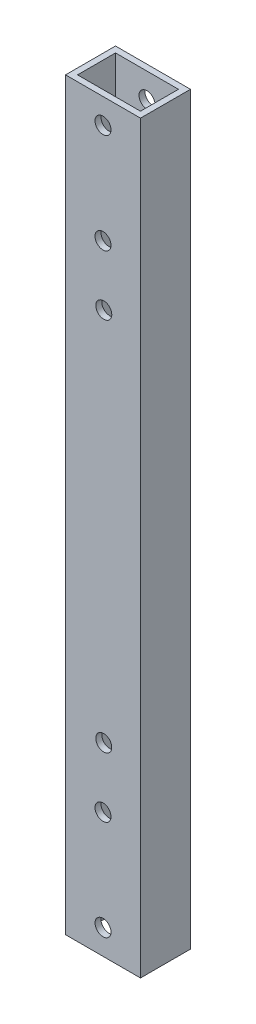
SolidWorks part; units mm, degrees
ref_plane "正面" through (0, 0, 0) normal (0, 0, 1) x (1, 0, 0)
ref_plane "平面" through (0, 0, 0) normal (0, 1, 0) x (1, 0, 0)
ref_plane "右側面" through (0, 0, 0) normal (1, 0, 0) x (0, 0, -1)
sketch "ｽｹｯﾁ1" plane through (0, 0, 0) normal (0, 1, 0) x (1, 0, 0)
  line L0 (-6.3, 3.8) -> (6.3, 3.8)
  line L5 (-7.5, 5) -> (7.5, 5)
  line L6 (-7.5, 5) -> (-7.5, -5)
  line L12 (-7.5, -5) -> (7.5, -5)
  line L13 (7.5, 5) -> (7.5, -5)
  line L14 (-7.5, 5) -> (7.5, -5) construction
  line L15 (-7.5, -5) -> (7.5, 5) construction
  line L16 (6.3, 3.8) -> (6.3, -3.8)
  line L17 (-6.3, -3.8) -> (6.3, -3.8)
  line L18 (-6.3, 3.8) -> (-6.3, -3.8)
  point P0 (0, 0)
  dimension "D1" = 10
  dimension "D2" = 15
  dimension "D3" = 1.2
extrude "ﾎﾞｽ - 押し出し1" add sketch "ｽｹｯﾁ1" along normal mid plane 149.02
sketch "ｽｹｯﾁ3" plane through (0, 0, 5) normal (0, 0, 1) x (1, 0, 0)
  line L0 (0, 74.51) -> (0, 69.51) construction
  line L1 (-7.5, 74.51) -> (7.5, 74.51) construction
  line L2 (0, 69.51) -> (0, 49.51) construction
  circle A0 centre (0, 49.51) radius 1.6
  circle A1 centre (0, 69.51) radius 1.6
  dimension "D3" = 3.2
  dimension "D4" = 3.2
  dimension "D1" = 5
  dimension "D2" = 20
extrude "ｶｯﾄ - 押し出し1" cut sketch "ｽｹｯﾁ3" against normal blind 10
mirror "ﾐﾗｰ1" about plane through (0, 0, 0) normal (0, 1, 0) of "ｶｯﾄ - 押し出し1"
sketch "ｽｹｯﾁ4" plane through (0, 0, -5) normal (0, 0, -1) x (-1, 0, 0)
  circle A0 centre (-0.155, 37.5791) radius 1.6 construction
  circle A1 centre (-0.15, -37.4209) radius 1.6 construction
  circle A2 centre (-0.155, 37.5791) radius 1.6
  circle A3 centre (-0.15, -37.4209) radius 1.6
extrude "ｶｯﾄ - 押し出し2" cut sketch "ｽｹｯﾁ4" against normal blind 10
